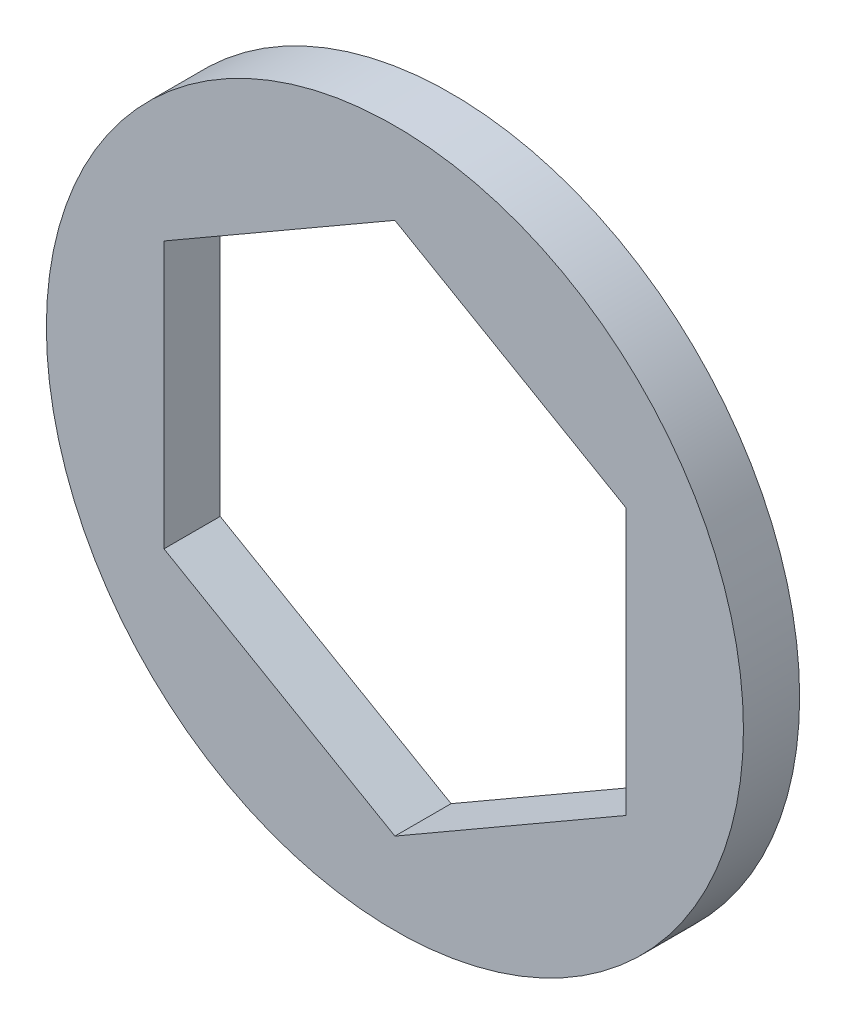
SolidWorks part; units mm, degrees
material "Nylon 101"
ref_plane "Front Plane" through (0, 0, 0) normal (0, 0, 1) x (1, 0, 0)
ref_plane "Top Plane" through (0, 0, 0) normal (0, 1, 0) x (1, 0, 0)
ref_plane "Right Plane" through (0, 0, 0) normal (1, 0, 0) x (0, 0, -1)
sketch "Sketch1" plane through (0, 0, 0) normal (0, 0, 1) x (1, 0, 0)
  line L1 (0, 7.7723) -> (-6.731, 3.8861)
  line L2 (-6.731, 3.8861) -> (-6.731, -3.8861)
  line L3 (-6.731, -3.8861) -> (0, -7.7723)
  line L4 (0, -7.7723) -> (6.731, -3.8861)
  line L5 (6.731, -3.8861) -> (6.731, 3.8861)
  line L6 (6.731, 3.8861) -> (0, 7.7723)
  circle A0 centre (0, 0) radius 10.16
  circle A1 centre (0, 0) radius 6.731 construction
  point P3 (0, 0)
  dimension "D1" = 13.462
  dimension "D2" = 20.32
extrude "Boss-Extrude1" add sketch "Sketch1" along normal mid plane 1.6383
